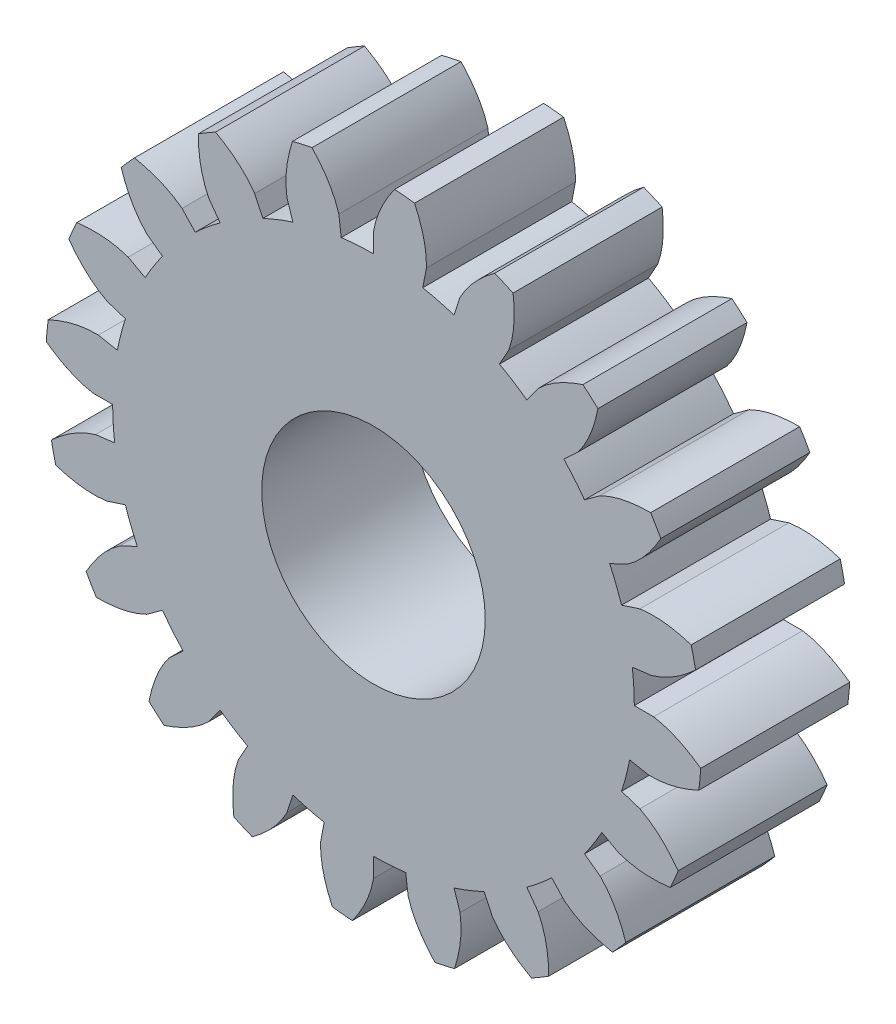
SolidWorks part; units mm, degrees
ref_plane "Front Plane" through (0, 0, 0) normal (0, 0, 1) x (1, 0, 0)
ref_plane "Top Plane" through (0, 0, 0) normal (0, 1, 0) x (1, 0, 0)
ref_plane "Right Plane" through (0, 0, 0) normal (1, 0, 0) x (0, 0, -1)
sketch "Sketch1" plane through (0, 0, 0) normal (0, 0, 1) x (1, 0, 0)
  line L0 (0, 18.794) -> (6.1917, 17.7448) construction
  line L1 (6.1917, 17.7448) -> (11.6921, 14.7142) construction
  line L2 (11.6921, 14.7142) -> (15.887, 10.0408) construction
  line L3 (15.887, 10.0408) -> (18.308, 4.2462) construction
  line L4 (6.1917, 17.7448) -> (0.2623, 19.8137) construction
  line L5 (11.6921, 14.7142) -> (1.8586, 22.5281) construction
  line L6 (15.887, 10.0408) -> (5.8217, 25.9667) construction
  line L7 (18.308, 4.2462) -> (12.6326, 28.7167) construction
  line L8 (0.3296, 19.9973) -> (3.4554, 19.6992) construction
  line L9 (0, 0) -> (1.8925, 19.8483) construction
  line L10 (0, 18.794) -> (0, 0)
  line L11 (0, 0) -> (3.5517, 18.4553)
  circle A0 centre (0, 0) radius 17.5
  circle A1 centre (0, 0) radius 22
  circle A2 centre (0, 0) radius 20 construction
  circle A3 centre (0, 0) radius 18.794 construction
  circle A4 centre (0, 0) radius 7.5
  spline S0 degree 3 poles (0, 18.794) (0.2289, 20.1881) (3.1768, 25.1592) (8.5939, 27.773) (12.6326, 28.7167) knots 0 0 0 0 0.250202 1 1 1 1
  spline S1 degree 3 poles (3.5517, 18.4553) (3.5904, 19.8675) (1.635, 25.3062) (-3.1905, 28.8966) (-6.978, 30.5865) knots 0 0 0 0 0.250202 1 1 1 1
  dimension "D1" = 44
  dimension "D2" = 35
  dimension "D3" = 37.588
  dimension "D4" = 40
  dimension "D5" = 6.28
  dimension "D10" = 15
  dimension "D6" = 6.28
  dimension "D7" = 12.56
  dimension "D8" = 18.84
  dimension "D9" = 25.12
extrude "Boss-Extrude1" add sketch "Sketch1" along normal blind 10 contours A4 L10 A0 L11 | A4 L11 A0 L10 | L11 S1 A1 S0 L10 A0
pattern_circular "CirPattern1" count 20 over 360 of "Boss-Extrude1"
